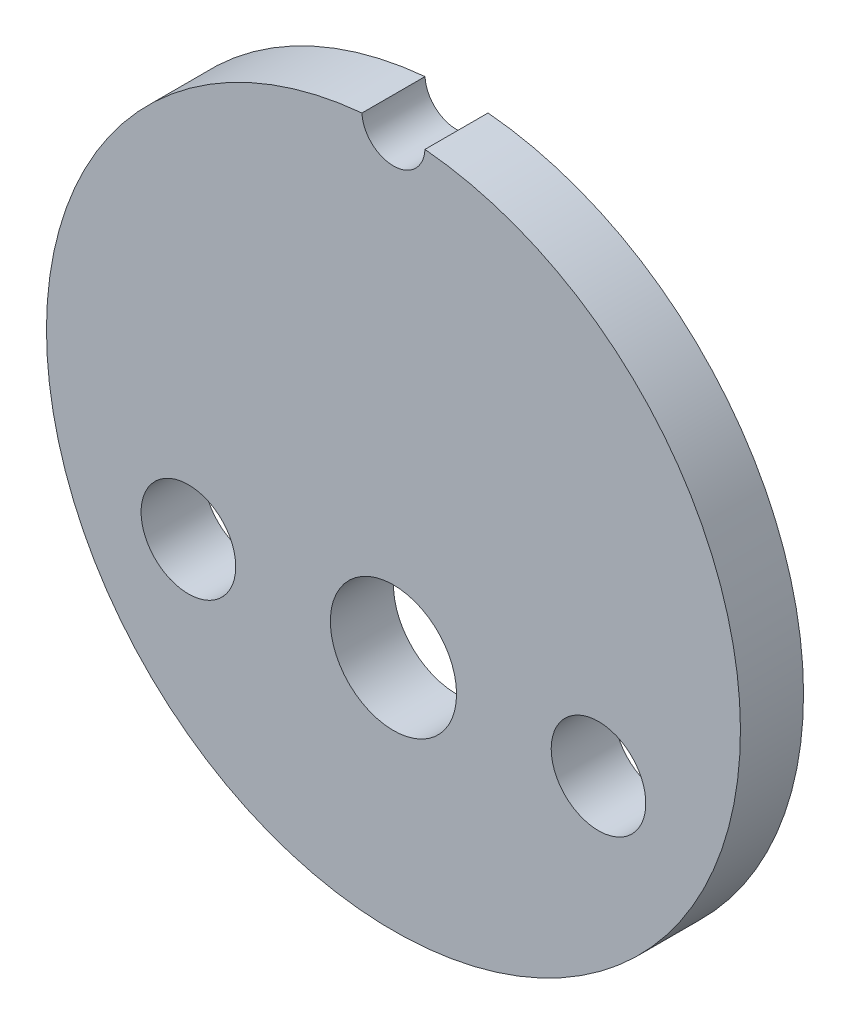
SolidWorks part; units mm, degrees
ref_plane "前视基准面" through (0, 0, 0) normal (0, 0, 1) x (1, 0, 0)
ref_plane "上视基准面" through (0, 0, 0) normal (0, 1, 0) x (1, 0, 0)
ref_plane "右视基准面" through (0, 0, 0) normal (1, 0, 0) x (0, 0, -1)
sketch "草图1" plane through (0, 0, 0) normal (0, 0, 1) x (1, 0, 0)
  line L0 (-0.5899, 5.3428) -> (-0.5899, 1.8428) construction
  line L1 (-0.5899, 1.8428) -> (-7.0899, 1.8428) construction
  circle A1 centre (-7.0899, 1.8428) radius 1.5
  circle A2 centre (5.9101, 1.8428) radius 1.5
  circle A3 centre (-0.5899, 1.8428) radius 2
  circle A4 centre (-0.5899, 5.3428) radius 11
  dimension "D1" = 3.5
  dimension "D3" = 22
  dimension "D2" = 6.5
extrude "凸台-拉伸1" add sketch "草图1" along normal blind 2
sketch "草图2" plane through (0, 0, 0) normal (0, 0, -1) x (-1, 0, 0)
  circle A0 centre (0.5899, 16.3428) radius 1
  circle A1 centre (0.5899, 5.3428) radius 11 construction
extrude "切除-拉伸1" cut sketch "草图2" against normal blind 10
